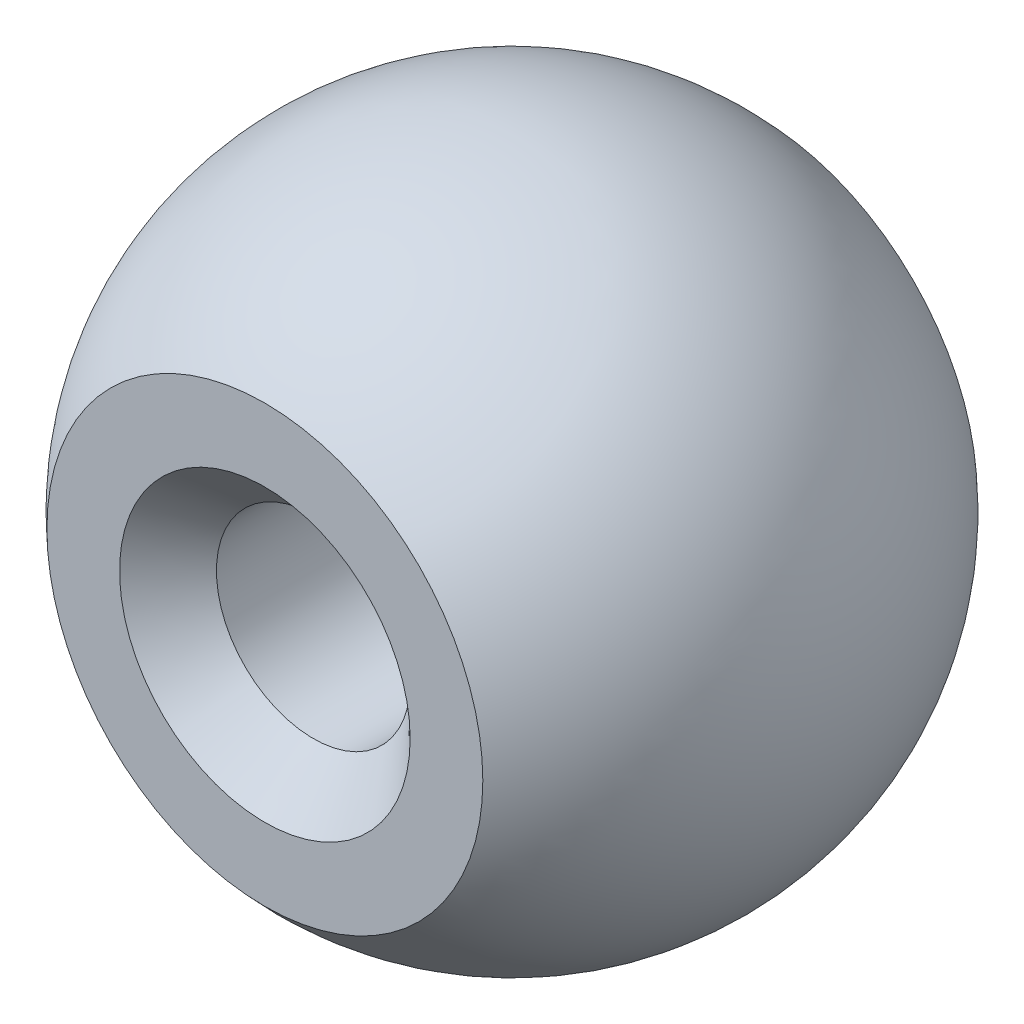
SolidWorks part; units mm, degrees
ref_plane "Front Plane" through (0, 0, 0) normal (0, 0, 1) x (1, 0, 0)
ref_plane "Top Plane" through (0, 0, 0) normal (0, 1, 0) x (1, 0, 0)
ref_plane "Right Plane" through (0, 0, 0) normal (1, 0, 0) x (0, 0, -1)
sketch "Sketch1" plane through (0, 0, 0) normal (0, 1, 0) x (1, 0, 0)
  line L0 (0, -5.1025) -> (0, 5.1025)
  line L5 (0, 0) -> (5.8868, -3.4105) construction
  line L7 (0, 5.1025) -> (4.5, 5.1025)
  line L8 (0, 0) -> (5.8868, 3.4105) construction
  line L9 (0, -5.1025) -> (4.5, -5.1025)
  arc A1 (4.5, -5.1025) -> (4.5, 5.1025) centre (0, 0) ccw
  dimension "D1" = 4.5
revolve "Revolve1" add sketch "Sketch1" angle 360 about L0
sketch "Sketch3" plane through (0, 0, 5.1025) normal (0, 0, 1) x (1, 0, 0)
  point P0 (0, 0)
hole_wizard "CSK for M1.6 Countersunk Flat Head Screw1" positions "3DSketch2" profile "Sketch4" countersink size "M1.6" standard "ISO" end condition through all
sketch3d "3DSketch2"
  point P0 (0, 0, 5.1025)
sketch "Sketch4" plane through (0, 0, 5.1025) normal (1, 0, 0) x (0, -1, 0)
  line L0 (0, 0) -> (0, 10.205)
  line L1 (0, 10.205) -> (2, 10.205)
  line L2 (2, 10.205) -> (2, 1)
  line L3 (2, 1) -> (3, 0)
  line L5 (3, 0) -> (0, 0)
  line L6 (-2, 1) -> (-3, 0) construction
  line L11 (0, -6.35) -> (0, 107.95) construction
  dimension "Thru Hole Dia." = 4
  dimension "Thru Hole Depth" = 10.205
  dimension "Near C'Sink Dia." = 6
  dimension "Near C'Sink Angle" = 90
